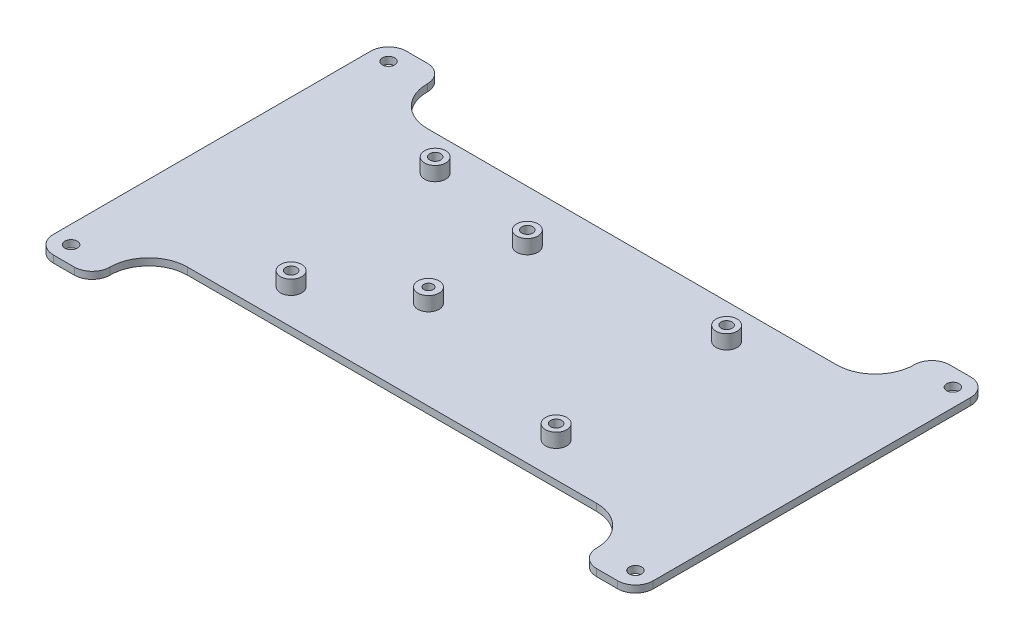
SolidWorks part; units mm, degrees
ref_plane "Plan de face" through (0, 0, 0) normal (0, 0, 1) x (1, 0, 0)
ref_plane "Plan de dessus" through (0, 0, 0) normal (0, 1, 0) x (1, 0, 0)
ref_plane "Plan de droite" through (0, 0, 0) normal (1, 0, 0) x (0, 0, -1)
sketch "Esquisse1" plane through (0, 0, 0) normal (0, 1, 0) x (1, 0, 0)
  line L8 (0, 0) -> (0, 20.0795) construction
  line L10 (0, 0) -> (-13.4196, 0) construction
  line L11 (80, 45) -> (80, 48.5397)
  line L12 (80, 48.5397) -> (80, 50.0397)
  line L13 (80, 45) -> (83.5397, 45)
  line L14 (83.5397, 45) -> (85.0397, 45)
  line L15 (80, 50.0397) -> (74.0397, 50.0397)
  line L16 (-80, 50.0397) -> (-74.0397, 50.0397)
  line L17 (-58, 34) -> (58, 34)
  line L18 (85.0397, 45) -> (85.0397, -45)
  line L19 (-85.0397, 45) -> (-85.0397, -45)
  line L20 (80, -50.0397) -> (74.0397, -50.0397)
  line L21 (-58, -34) -> (58, -34)
  line L22 (-80, -50.0397) -> (-74.0397, -50.0397)
  arc A5 (-80, 50.0397) -> (-85.0397, 45) centre (-80, 45) ccw
  circle A6 centre (80, 45) radius 3.5397 construction
  arc A8 (-74.0397, 50.0397) -> (-69, 45) centre (-74.0397, 45) cw
  arc A13 (-69, 45) -> (-58, 34) centre (-58, 45) ccw
  arc A14 (69, 45) -> (58, 34) centre (58, 45) cw
  arc A15 (74.0397, 50.0397) -> (69, 45) centre (74.0397, 45) ccw
  arc A16 (80, 50.0397) -> (85.0397, 45) centre (80, 45) cw
  arc A17 (80, -50.0397) -> (85.0397, -45) centre (80, -45) ccw
  arc A18 (74.0397, -50.0397) -> (69, -45) centre (74.0397, -45) cw
  arc A19 (69, -45) -> (58, -34) centre (58, -45) ccw
  arc A20 (-69, -45) -> (-58, -34) centre (-58, -45) cw
  arc A21 (-74.0397, -50.0397) -> (-69, -45) centre (-74.0397, -45) ccw
  arc A22 (-80, -50.0397) -> (-85.0397, -45) centre (-80, -45) cw
  circle A23 centre (-80, -45) radius 1.75
  circle A24 centre (-80, 45) radius 1.75
  circle A25 centre (80, -45) radius 1.75
  circle A26 centre (80, 45) radius 1.75
  point P11 (86, -50)
  point P16 (-86, 50)
  point P19 (-86, -50)
  point P22 (0, 34)
  point P35 (85.0397, 0)
  point P50 (-85.0397, 0)
extrude "Boss.-Extru.1" add sketch "Esquisse1" along normal blind 2 contours A26 L11 L12 L15 A15 A14 L17 A13 A8 L16 A5 L19 A22 L22 A21 A20 L21 A19 A18 L20 A17 L18 L14 L13 A25 A24 A23 | A26 L13 L14 A16 L12 L11
sketch "Esquisse2" plane through (0, 2, 0) normal (0, 1, 0) x (1, 0, 0)
  circle A1 centre (-14.9479, 19.2915) radius 3
  circle A2 centre (-14.9479, -8.7247) radius 3
  circle A3 centre (-38.4556, -24.1662) radius 3
  circle A4 centre (36.6776, -24.1662) radius 3
  circle A5 centre (36.6776, 24.17) radius 3
  circle A6 centre (-45.9486, 24.17) radius 3
  circle A7 centre (-45.9486, 24.17) radius 1.5621
  circle A8 centre (-14.9479, 19.2915) radius 1.5621
  circle A9 centre (36.6776, 24.17) radius 1.5621
  circle A10 centre (36.6776, -24.1662) radius 1.5621
  circle A11 centre (-14.9479, -8.7247) radius 1.3153
  circle A12 centre (-38.4556, -24.1662) radius 1.5621
extrude "Boss.-Extru.2" add sketch "Esquisse2" along normal blind 4
sketch "Esquisse4" plane through (0, 2, 0) normal (0, 1, 0) x (1, 0, 0)
  circle A0 centre (-45.9486, 24.17) radius 1.5621
  circle A1 centre (-14.9479, 19.2915) radius 1.5621
  circle A2 centre (36.6776, 24.17) radius 1.5621
  circle A3 centre (36.6776, -24.1662) radius 1.5621
  circle A4 centre (-14.9479, -8.7247) radius 1.3153
  circle A5 centre (-38.4556, -24.1662) radius 1.5621
extrude "Enlèv. mat.-Extru.1" cut sketch "Esquisse4" against normal blind 4
